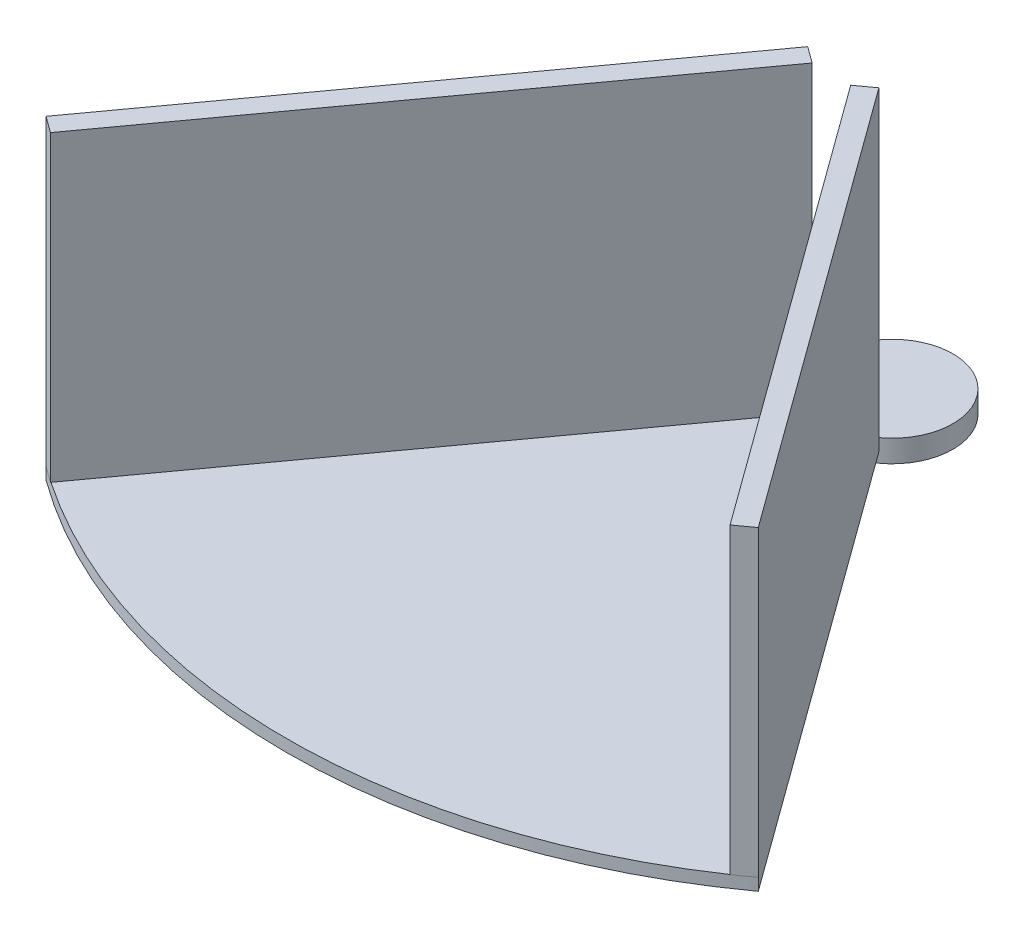
SolidWorks part; units mm, degrees
ref_plane "Front Plane" through (0, 0, 0) normal (0, 0, 1) x (1, 0, 0)
ref_plane "Top Plane" through (0, 0, 0) normal (0, 1, 0) x (1, 0, 0)
ref_plane "Right Plane" through (0, 0, 0) normal (1, 0, 0) x (0, 0, -1)
sketch "Sketch1" plane through (0, 0, 0) normal (0, 1, 0) x (1, 0, 0)
  circle A0 centre (0, 0) radius 3.175
  circle A1 centre (0, 0) radius 6
  dimension "D1" = 6.35
  dimension "D2" = 12
extrude "Boss-Extrude1" add sketch "Sketch1" along normal blind 16
sketch "Sketch2" plane through (0, 16, 0) normal (0, 1, 0) x (1, 0, 0)
  circle A0 centre (0, 0) radius 30
  dimension "D1" = 60
extrude "Boss-Extrude2" add sketch "Sketch2" along normal blind 5
sketch "Sketch3" plane through (0, 21, 0) normal (0, 1, 0) x (1, 0, 0)
  line L2 (17.6336, -24.2705) -> (176.3356, -242.7051)
  line L3 (-17.6336, -24.2705) -> (-176.3356, -242.7051)
  arc A0 (17.6336, -24.2705) -> (-17.6336, -24.2705) centre (0, 0) ccw
  arc A1 (-176.3356, -242.7051) -> (176.3356, -242.7051) centre (0, 0) ccw
  dimension "D1" = 60
  dimension "D2" = 600
extrude "Boss-Extrude3" add sketch "Sketch3" along normal blind 6
sketch "Sketch4" plane through (0, 27, 0) normal (0, 1, 0) x (1, 0, 0)
  line L0 (-176.3356, -242.7051) -> (-17.6336, -24.2705)
  line L1 (-176.3356, -242.7051) -> (-168.2454, -248.583)
  line L2 (-17.6336, -24.2705) -> (-9.5434, -30.1484)
  line L3 (-168.2454, -248.583) -> (-9.5434, -30.1484)
  line L4 (17.6336, -24.2705) -> (176.3356, -242.7051)
  line L5 (17.6336, -24.2705) -> (9.5434, -30.1484)
  line L6 (176.3356, -242.7051) -> (168.2454, -248.583)
  line L7 (9.5434, -30.1484) -> (168.2454, -248.583)
  dimension "D1" = 10
  dimension "D2" = 10
extrude "Boss-Extrude4" add sketch "Sketch4" along normal blind 150
